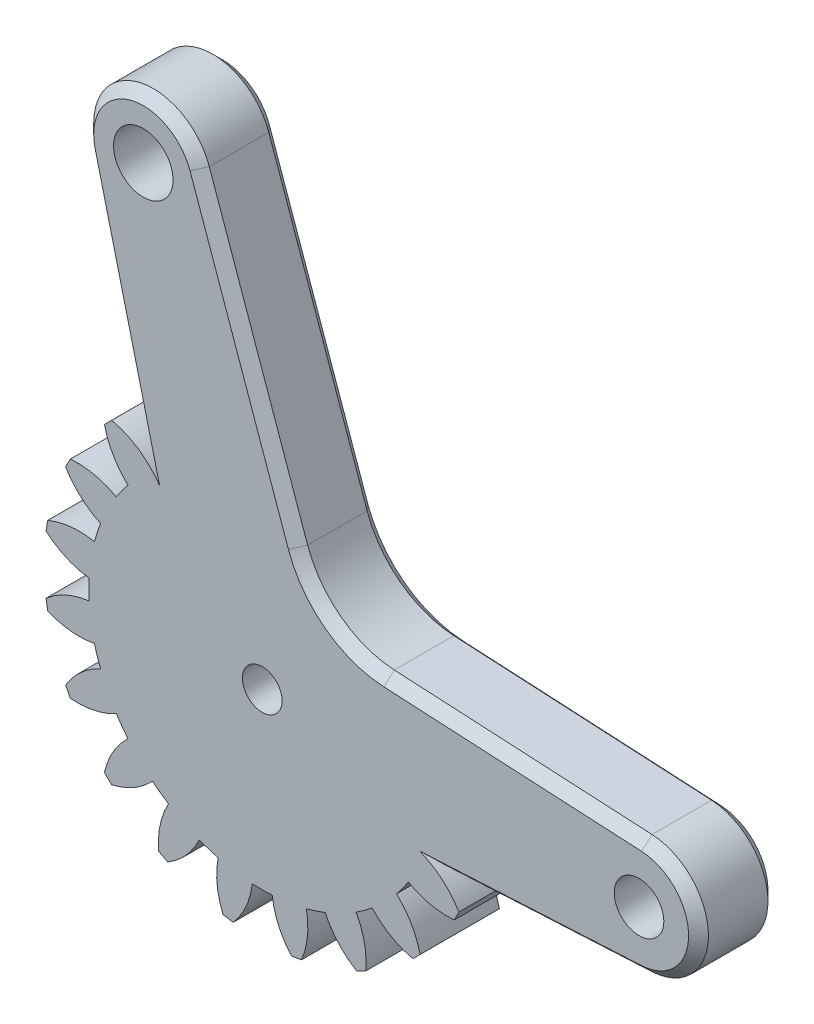
SolidWorks part; units mm, degrees
ref_plane "Alzado" through (0, 0, 0) normal (0, 0, 1) x (1, 0, 0)
ref_plane "Planta" through (0, 0, 0) normal (0, 1, 0) x (1, 0, 0)
ref_plane "Vista lateral" through (0, 0, 0) normal (1, 0, 0) x (0, 0, -1)
sketch "Croquis7" plane through (0, 0, 0) normal (0, 0, 1) x (1, 0, 0)
  circle A0 centre (0, 0) radius 11
  circle A1 centre (0, 0) radius 1
  point P4 (0, 0)
  dimension "D1" = 22
extrude "Saliente-Extruir4" add sketch "Croquis7" against normal blind 4
sketch "Croquis10" plane through (0, 0, 0) normal (0, 0, 1) x (1, 0, 0)
  line L1 (0, 0) -> (0, 107) construction
  line L2 (0, 0) -> (-0.8511, 9.9637) construction
  line L3 (0, 0) -> (-3.1206, 19.7028) construction
  line L4 (-0.8511, 9.9637) -> (-1.5603, 9.8514) construction
  arc A0 (0.4999, 8.7347) -> (-0.4999, 8.7347) centre (0, 0) ccw
  arc A1 (1.4852, 10.9249) -> (-1.4852, 10.9249) centre (0, 0) ccw
  circle A2 centre (0, 0) radius 10 construction
  circle A3 centre (0, 0) radius 9.3969 construction
  arc A4 (-0.4999, 8.7347) -> (-1.4852, 10.9249) centre (-4.4722, 8.2645) ccw
  arc A5 (1.4852, 10.9249) -> (0.4999, 8.7347) centre (4.4722, 8.2645) ccw
  point P2 (0, 0)
  dimension "Root_dia" = 17.498
  dimension "Overcut_dia" = 22.0508
  dimension "Pitch_dia" = 20
  dimension "Base_dia" = 18.7939
  dimension "Flank_rad" = 4
  dimension "Half_ang" = 9
  dimension "Half_CT" = 0.7181
extrude "Cortar-Extruir3" cut sketch "Croquis10" against normal through all
pattern_circular "MatrizC3" count 20 over 360 about axis through (0, 0, 0) along (0, 0, 1) of "Cortar-Extruir3"
sketch "Croquis9" plane through (0, 0, 0) normal (0, 0, 1) x (1, 0, 0)
  line L0 (0, 0) -> (16185.8284, 0) construction
  line L1 (0, 0) -> (19, 0) construction
  line L2 (0.2105, 3.9945) -> (19.1579, 2.9958)
  line L3 (0.2105, -3.9945) -> (19.1579, -2.9958)
  circle A0 centre (0, 0) radius 1
  circle A1 centre (19, 0) radius 1.25
  arc A3 (19.1579, -2.9958) -> (19.1579, 2.9958) centre (19, 0) ccw
  arc A4 (0.2105, 3.9945) -> (0.2105, -3.9945) centre (0, 0) ccw
  point P5 (9.5, 0)
  dimension "D2" = 3
  dimension "D3" = 2.5
  dimension "D4" = 2
  dimension "D5" = 8
  dimension "D1" = 19
extrude "Saliente-Extruir5" add sketch "Croquis9" against normal blind 4
sketch "Croquis2" plane through (0, 0, -4) normal (0, 0, 1) x (1, 0, 0)
  line L6 (-3.1711, 20.9987) -> (3.7719, 1.3316)
  line L7 (-8.9115, 19.2766) -> (-3.882, -0.9646)
  circle A1 centre (0, 0) radius 1
  circle A2 centre (-6, 20) radius 1.5
  arc A3 (-3.1711, 20.9987) -> (-8.9115, 19.2766) centre (-6, 20) ccw
  arc A4 (-3.882, -0.9646) -> (3.7719, 1.3316) centre (0, 0) ccw
  dimension "D1" = 3
  dimension "D2" = 3
  dimension "D3" = 20
  dimension "D4" = 6
extrude "Saliente-Extruir2" add sketch "Croquis2" along normal through all
sketch "Croquis11" plane through (0, 0, -4) normal (0, 0, -1) x (-1, 0, 0)
  line L0 (-0.7806, 9.8047) -> (-1.7886, 6.9494)
  line L1 (-6.1599, 3.6809) -> (-8.789, 3.5423)
  line L2 (-0.7806, 9.8047) -> (-0.366, 17.3197)
  line L3 (-0.366, 17.3197) -> (-17.0397, 17.3197)
  line L4 (-17.0397, 17.3197) -> (-14.1548, 5.1933)
  line L5 (-14.1548, 5.1933) -> (-8.789, 3.5423)
  line L6 (-19.1579, 2.9958) -> (-8.789, 3.5423) construction
  arc A0 (-1.7886, 6.9494) -> (-6.1599, 3.6809) centre (-6.4183, 8.5837) cw
extrude "Cortar-Extruir4" cut sketch "Croquis11" against normal through all
chamfer "Chaflán1" distance 0.5 angle 45 14 edges at (13.9735, -3.2691, -4) (13.9735, -3.2691, 0) (22, 0, 0) (22, 0, -4) (12.6589, 3.3384, -4) (12.6589, 3.3384, 0) (-7.3996, 13.1919, -4) (3.4782, 4.6517, -4) (-6.862, 22.8735, -4) (-0.6912, 13.974, -4) (-7.3996, 13.1919, 0) (-6.862, 22.8735, 0) (-0.6912, 13.974, 0) (3.4782, 4.6517, 0)
